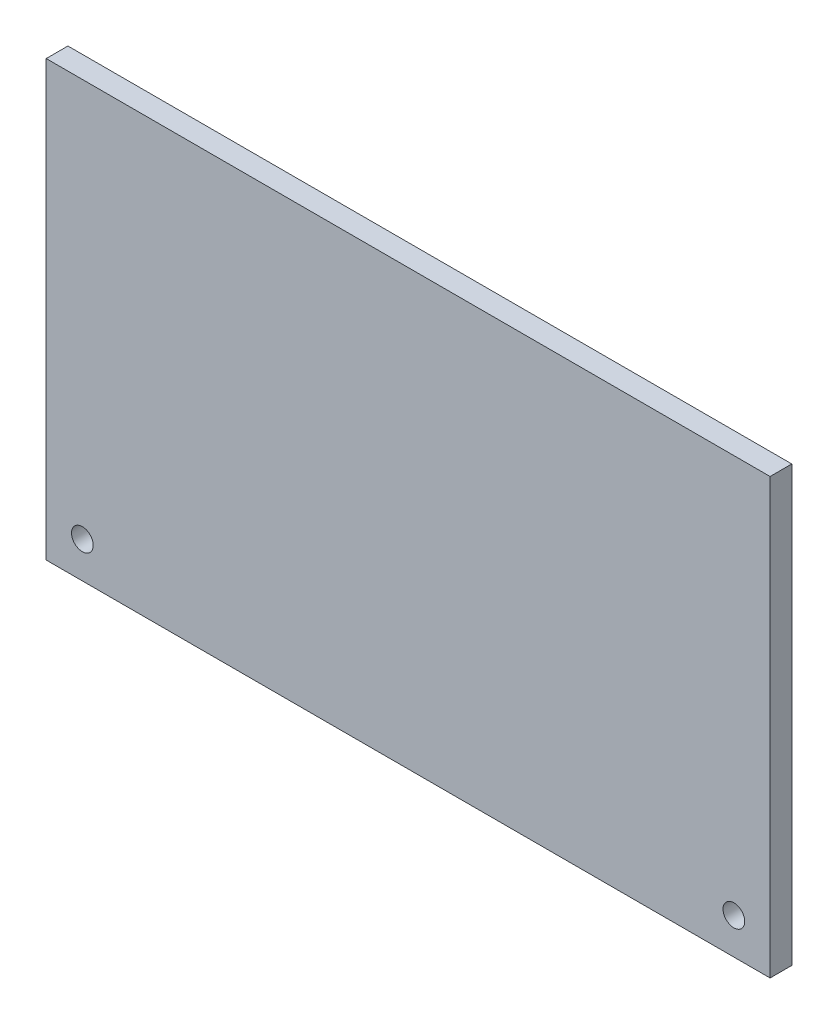
SolidWorks part; units mm, degrees
ref_plane "Front Plane" through (0, 0, 0) normal (0, 0, 1) x (1, 0, 0)
ref_plane "Top Plane" through (0, 0, 0) normal (0, 1, 0) x (1, 0, 0)
ref_plane "Right Plane" through (0, 0, 0) normal (1, 0, 0) x (0, 0, -1)
sketch "Sketch1" plane through (0, 0, 0) normal (0, 0, 1) x (1, 0, 0)
  line L1 (-57.4956, 34.0388) -> (42.5044, 34.0388)
  line L2 (-57.4956, 34.0388) -> (-57.4956, -25.9612)
  line L3 (-57.4956, -25.9612) -> (42.5044, -25.9612)
  line L4 (42.5044, 34.0388) -> (42.5044, -25.9612)
  dimension "D1" = 100
  dimension "D2" = 60
extrude "Boss-Extrude1" add sketch "Sketch1" along normal blind 3
sketch "Sketch2" plane through (0, 0, 3) normal (0, 0, 1) x (1, 0, 0)
  circle A0 centre (37.5044, -20.9612) radius 1.5
  circle A1 centre (-52.5, -20.9612) radius 1.5
extrude "Cut-Extrude1" cut sketch "Sketch2" against normal blind 3
